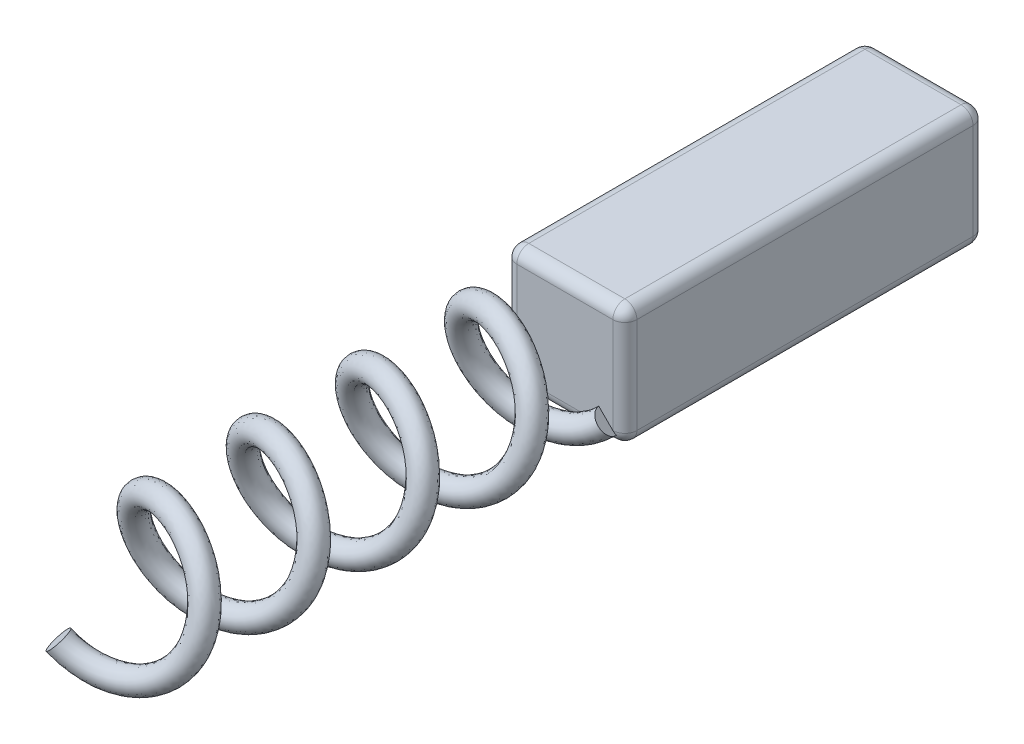
SolidWorks part; units mm, degrees
ref_plane "Front Plane" through (0, 0, 0) normal (0, 0, 1) x (1, 0, 0)
ref_plane "Top Plane" through (0, 0, 0) normal (0, 1, 0) x (1, 0, 0)
ref_plane "Right Plane" through (0, 0, 0) normal (1, 0, 0) x (0, 0, -1)
sketch "Sketch1" plane through (0, 0, 0) normal (0, 0, 1) x (1, 0, 0)
  line L1 (2.5, 2.5) -> (-2.5, 2.5)
  line L2 (2.5, 2.5) -> (2.5, -2.5)
  line L3 (2.5, -2.5) -> (-2.5, -2.5)
  line L4 (-2.5, 2.5) -> (-2.5, -2.5)
  line L5 (2.5, 2.5) -> (-2.5, -2.5) construction
  line L6 (2.5, -2.5) -> (-2.5, 2.5) construction
  point P0 (0, 0)
  dimension "D1" = 5
  dimension "D2" = 5
extrude "Boss-Extrude1" add sketch "Sketch1" along normal blind 15
fillet "Fillet1" radius 0.5 12 edges at (-2.5, 2.5, 7.5) (-2.5, -2.5, 7.5) (2.5, -2.5, 7.5) (2.5, 2.5, 7.5) (0, 2.5, 0) (2.5, 0, 0) (0, -2.5, 0) (-2.5, 0, 0) (-2.5, 0, 15) (0, -2.5, 15) (2.5, 0, 15) (0, 2.5, 15)
sketch "Sketch2" plane through (0, 0, 15) normal (0, 0, 1) x (1, 0, 0)
  circle A0 centre (0, 0) radius 2.5
curve "Helix/Spiral1" pitch 4.5455 height 19.3182 turns 4.25
sweep "Sweep1" add path "Helix/Spiral1" circular profile diameter 1 parameters "D3"=1
